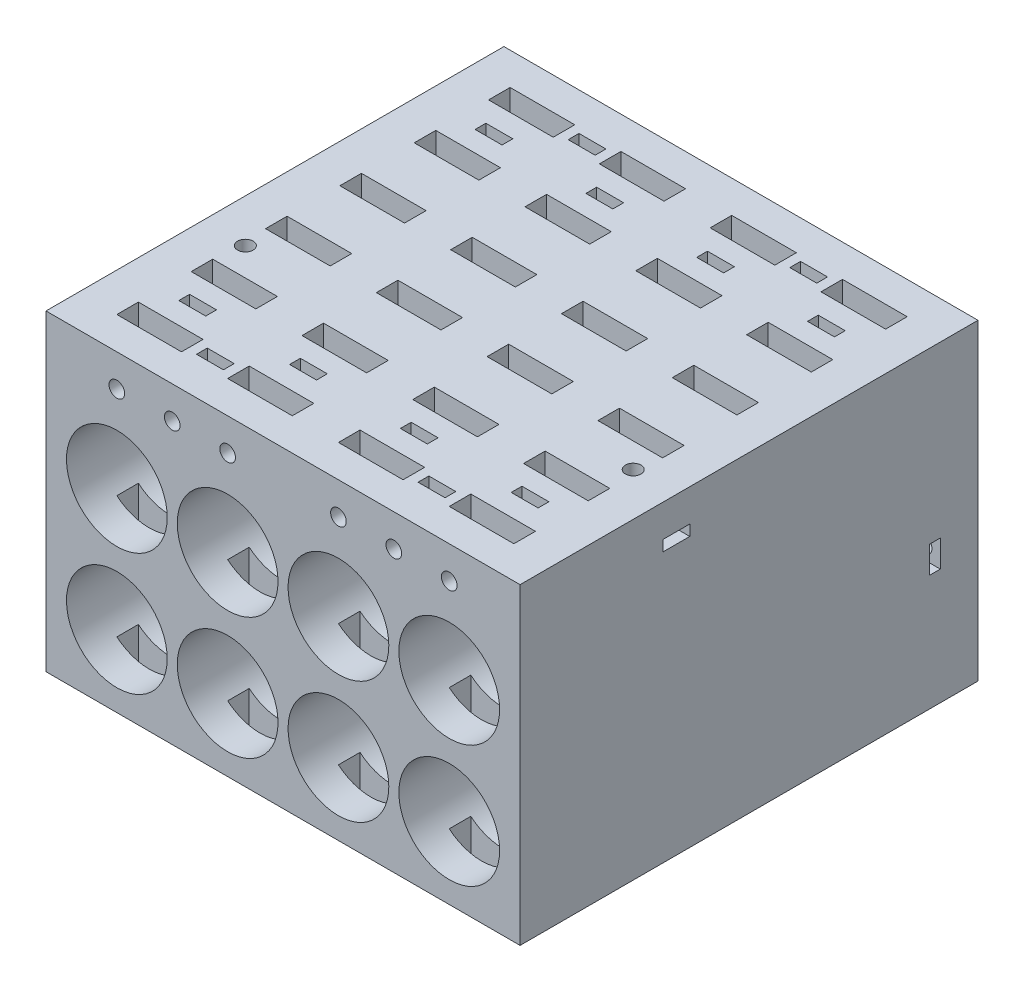
SolidWorks part; units mm, degrees
material "ABS"
ref_plane "Front Plane" through (0, 0, 0) normal (0, 0, 1) x (1, 0, 0)
ref_plane "Top Plane" through (0, 0, 0) normal (0, 1, 0) x (1, 0, 0)
ref_plane "Right Plane" through (0, 0, 0) normal (1, 0, 0) x (0, 0, -1)
sketch "Sketch1" plane through (0, 0, 0) normal (0, 0, 1) x (1, 0, 0)
  line L1 (0, 0) -> (88, 0)
  line L2 (0, 0) -> (0, 58)
  line L3 (0, 58) -> (88, 58)
  line L4 (88, 0) -> (88, 58)
  dimension "D1" = 88
  dimension "D2" = 58
extrude "Boss-Extrude1" add sketch "Sketch1" along normal blind 10
sketch "Sketch2" plane through (0, 0, 10) normal (0, 0, 1) x (1, 0, 0)
  line L0 (3.8, 58) -> (3.8, 0) construction
  line L1 (88, 58) -> (0, 58) construction
  line L2 (0, 0) -> (88, 0) construction
  line L3 (84.2, 58) -> (84.2, 0) construction
  line L4 (0, 4) -> (3.8, 4) construction
  line L5 (0, 58) -> (0, 0) construction
  line L6 (3.8, 4) -> (84.2, 4) construction
  line L7 (84.2, 4) -> (88, 4) construction
  line L8 (88, 0) -> (88, 58) construction
  line L9 (13.15, 13.35) -> (33.7167, 13.35) construction
  line L10 (33.7167, 13.35) -> (54.2833, 13.35) construction
  line L11 (54.2833, 13.35) -> (74.85, 13.35) construction
  line L12 (3.8, 22.7) -> (84.2, 22.7) construction
  line L13 (3.8, 26.7) -> (84.2, 26.7) construction
  line L14 (3.8, 45.4) -> (84.2, 45.4) construction
  line L15 (13.15, 36.05) -> (33.7167, 36.05) construction
  line L16 (33.7167, 36.05) -> (54.2833, 36.05) construction
  line L17 (54.2833, 36.05) -> (74.85, 36.05) construction
  line L19 (0, 0) -> (88, 0)
  line L20 (0, 0) -> (0, 58)
  line L21 (0, 58) -> (88, 58)
  line L22 (88, 0) -> (88, 58)
  circle A0 centre (13.15, 13.35) radius 9.35
  circle A1 centre (33.7167, 13.35) radius 9.35
  circle A2 centre (54.2833, 13.35) radius 9.35
  circle A3 centre (74.85, 13.35) radius 9.35
  circle A4 centre (13.15, 36.05) radius 9.35
  circle A5 centre (33.7167, 36.05) radius 9.35
  circle A6 centre (54.2833, 36.05) radius 9.35
  circle A7 centre (74.85, 36.05) radius 9.35
  dimension "D1" = 18.7
  dimension "D2" = 3.8
  dimension "D3" = 4
  dimension "D4" = 4
extrude "Boss-Extrude2" add sketch "Sketch2" along normal blind 75
sketch "Sketch3" plane through (0, 0, 0) normal (0, -1, 0) x (1, 0, 0)
  line L0 (84.2, 10) -> (65.5, 10) construction
  line L1 (63.6333, 10) -> (44.9333, 10) construction
  line L2 (43.0667, 10) -> (24.3667, 10) construction
  line L3 (22.5, 10) -> (3.8, 10) construction
  line L4 (84.2, 10) -> (65.5, 10) construction
  line L5 (63.6333, 10) -> (44.9333, 10) construction
  line L6 (43.0667, 10) -> (24.3667, 10) construction
  line L7 (22.5, 10) -> (3.8, 10) construction
  line L8 (80.85, 10) -> (80.85, 6)
  line L9 (80.85, 6) -> (68.85, 6)
  line L10 (68.85, 6) -> (68.85, 10)
  line L11 (60.2833, 10) -> (60.2833, 6)
  line L12 (60.2833, 6) -> (48.2833, 6)
  line L13 (48.2833, 6) -> (48.2833, 10)
  line L14 (39.7167, 10) -> (39.7167, 6)
  line L15 (39.7167, 6) -> (27.7167, 6)
  line L16 (27.7167, 6) -> (27.7167, 10)
  line L17 (19.15, 10) -> (19.15, 6)
  line L18 (19.15, 6) -> (7.15, 6)
  line L19 (7.15, 6) -> (7.15, 10)
  line L20 (80.85, 10) -> (68.85, 10)
  line L21 (60.2833, 10) -> (48.2833, 10)
  line L22 (39.7167, 10) -> (27.7167, 10)
  line L23 (19.15, 10) -> (7.15, 10)
  line L24 (0, 85) -> (88, 85) construction
  line L25 (7.15, 79) -> (19.15, 79)
  line L26 (7.15, 79) -> (7.15, 75)
  line L27 (7.15, 75) -> (19.15, 75)
  line L28 (19.15, 79) -> (19.15, 75)
  line L29 (27.7167, 79) -> (39.7167, 79)
  line L30 (27.7167, 79) -> (27.7167, 75)
  line L31 (27.7167, 75) -> (39.7167, 75)
  line L32 (39.7167, 79) -> (39.7167, 75)
  line L33 (48.2833, 79) -> (60.2833, 79)
  line L34 (48.2833, 79) -> (48.2833, 75)
  line L35 (48.2833, 75) -> (60.2833, 75)
  line L36 (60.2833, 79) -> (60.2833, 75)
  line L37 (68.85, 79) -> (80.85, 79)
  line L38 (68.85, 79) -> (68.85, 75)
  line L39 (68.85, 75) -> (80.85, 75)
  line L40 (80.85, 79) -> (80.85, 75)
  point P24 (74.85, 6)
  point P25 (74.85, 10)
  point P26 (54.2833, 6)
  point P27 (54.2833, 10)
  point P28 (33.7167, 6)
  point P29 (33.7167, 10)
  point P30 (13.15, 6)
  point P31 (13.15, 10)
  dimension "D1" = 4
  dimension "D2" = 12
  dimension "D3" = 10
extrude "Cut-Extrude1" cut sketch "Sketch3" against normal through all
hole_wizard "M2.5 Clearance Hole1" positions "Sketch4" profile "Sketch5" hole size "M2.5" standard "ANSI Metric"
sketch "Sketch4" plane through (0, 0, 85) normal (0, 0, 1) x (1, 0, 0)
  line L0 (0, 52) -> (88, 52) construction
  line L1 (0, 58) -> (0, 0) construction
  line L2 (88, 0) -> (88, 58) construction
  line L13 (13.15, 13.35) -> (13.15, 58) construction
  line L14 (88, 58) -> (0, 58) construction
  line L16 (33.7167, 13.35) -> (33.7167, 58) construction
  line L18 (54.2833, 13.35) -> (54.2833, 58) construction
  line L20 (74.85, 13.35) -> (74.85, 58) construction
  point P68 (13.15, 52)
  point P70 (33.7167, 52)
  point P72 (54.2833, 52)
  point P74 (74.85, 52)
  dimension "D1" = 6
sketch "Sketch5" plane through (74.85, 52, 85) normal (1, 0, 0) x (0, -1, 0)
  line L0 (0, 0) -> (0, 22.8712)
  line L1 (0, 22.8712) -> (1.45, 22)
  line L2 (1.45, 22) -> (1.45, 0)
  line L5 (1.45, 0) -> (0, 0)
  line L10 (0, 22.8712) -> (-1.45, 22) construction
  line L11 (0, -6.35) -> (0, 107.95) construction
  dimension "Hole Dia." = 2.9
  dimension "Hole Depth" = 22
  dimension "Drill Angle" = 118
hole_wizard "M2.5 Clearance Hole2" positions "Sketch6" profile "Sketch7" hole size "M2.5" standard "ANSI Metric"
sketch "Sketch6" plane through (0, 0, 0) normal (0, 0, -1) x (-1, 0, 0)
  line L0 (-88, 52) -> (0, 52) construction
  line L1 (-88, 0) -> (-88, 58) construction
  line L2 (0, 58) -> (0, 0) construction
  line L4 (-88, 58) -> (0, 58) construction
  line L5 (-19.15, 58) -> (-7.15, 58) construction
  line L6 (-39.7167, 58) -> (-27.7167, 58) construction
  line L7 (-60.2833, 58) -> (-48.2833, 58) construction
  line L8 (-80.85, 58) -> (-68.85, 58) construction
  line L9 (-19.15, 58) -> (-7.15, 58) construction
  line L10 (-39.7167, 58) -> (-27.7167, 58) construction
  line L11 (-60.2833, 58) -> (-48.2833, 58) construction
  line L12 (-80.85, 58) -> (-68.85, 58) construction
  point P0 (-74.85, 52)
  point P2 (-54.2833, 52)
  point P4 (-33.7167, 52)
  point P6 (-13.15, 52)
  point P33 (-74.85, 58)
  point P35 (-54.2833, 58)
  point P37 (-33.7167, 58)
  point P38 (-13.15, 58)
  dimension "D1" = 6
sketch "Sketch7" plane through (74.85, 52, 0) normal (1, 0, 0) x (0, 1, 0)
  line L0 (0, 0) -> (0, 22.8712)
  line L1 (0, 22.8712) -> (1.45, 22)
  line L2 (1.45, 22) -> (1.45, 0)
  line L5 (1.45, 0) -> (0, 0)
  line L10 (0, 22.8712) -> (-1.45, 22) construction
  line L11 (0, -6.35) -> (0, 107.95) construction
  dimension "Hole Dia." = 2.9
  dimension "Hole Depth" = 22
  dimension "Drill Angle" = 118
sketch "Sketch8" plane through (0, 58, 0) normal (0, 1, 0) x (1, 0, 0)
  line L0 (68.85, -75) -> (80.85, -75) construction
  line L1 (77.35, -71) -> (72.35, -71)
  line L2 (77.35, -71) -> (77.35, -69)
  line L3 (77.35, -69) -> (72.35, -69)
  line L4 (72.35, -71) -> (72.35, -69)
  line L5 (88, -42.5) -> (0, -42.5) construction
  line L6 (88, -85) -> (88, 0) construction
  line L7 (0, -85) -> (0, 0) construction
  line L8 (44, -85) -> (44, 0) construction
  line L9 (88, -85) -> (0, -85) construction
  line L10 (88, 0) -> (0, 0) construction
  line L11 (48.2833, -75) -> (60.2833, -75) construction
  line L12 (56.7833, -71) -> (51.7833, -71)
  line L13 (56.7833, -71) -> (56.7833, -69)
  line L14 (56.7833, -69) -> (51.7833, -69)
  line L15 (51.7833, -71) -> (51.7833, -69)
  line L16 (56.7833, -16) -> (51.7833, -16)
  line L17 (51.7833, -14) -> (51.7833, -16)
  line L18 (56.7833, -14) -> (51.7833, -14)
  line L19 (56.7833, -14) -> (56.7833, -16)
  line L20 (77.35, -16) -> (72.35, -16)
  line L21 (72.35, -14) -> (72.35, -16)
  line L22 (77.35, -14) -> (72.35, -14)
  line L23 (77.35, -14) -> (77.35, -16)
  line L24 (31.2167, -14) -> (31.2167, -16)
  line L25 (31.2167, -14) -> (36.2167, -14)
  line L26 (36.2167, -14) -> (36.2167, -16)
  line L27 (31.2167, -16) -> (36.2167, -16)
  line L28 (10.65, -14) -> (10.65, -16)
  line L29 (10.65, -14) -> (15.65, -14)
  line L30 (15.65, -14) -> (15.65, -16)
  line L31 (10.65, -16) -> (15.65, -16)
  line L32 (10.65, -69) -> (15.65, -69)
  line L33 (15.65, -71) -> (15.65, -69)
  line L34 (10.65, -71) -> (15.65, -71)
  line L35 (10.65, -71) -> (10.65, -69)
  line L36 (31.2167, -69) -> (36.2167, -69)
  line L37 (36.2167, -71) -> (36.2167, -69)
  line L38 (31.2167, -71) -> (36.2167, -71)
  line L39 (31.2167, -71) -> (31.2167, -69)
  line L40 (68.85, -8) -> (60.2833, -8) construction
  line L41 (68.85, -10) -> (68.85, -6) construction
  line L42 (60.2833, -6) -> (60.2833, -10) construction
  line L43 (27.7167, -8) -> (19.15, -8) construction
  line L44 (27.7167, -10) -> (27.7167, -6) construction
  line L45 (19.15, -6) -> (19.15, -10) construction
  line L46 (64.5667, -8) -> (64.5667, 0) construction
  line L47 (23.4333, -8) -> (23.4333, 0) construction
  line L48 (48.2833, -8) -> (39.7167, -8) construction
  line L49 (67.0667, -7) -> (62.0667, -7)
  line L50 (67.0667, -7) -> (67.0667, -9)
  line L51 (67.0667, -9) -> (62.0667, -9)
  line L52 (62.0667, -7) -> (62.0667, -9)
  line L53 (67.0667, -7) -> (62.0667, -9) construction
  line L54 (67.0667, -9) -> (62.0667, -7) construction
  line L55 (25.9333, -7) -> (20.9333, -7)
  line L56 (25.9333, -7) -> (25.9333, -9)
  line L57 (25.9333, -9) -> (20.9333, -9)
  line L58 (20.9333, -7) -> (20.9333, -9)
  line L59 (25.9333, -7) -> (20.9333, -9) construction
  line L60 (25.9333, -9) -> (20.9333, -7) construction
  line L61 (48.2833, -10) -> (48.2833, -6) construction
  line L62 (39.7167, -6) -> (39.7167, -10) construction
  line L63 (19.15, -77) -> (27.7167, -77) construction
  line L64 (19.15, -75) -> (19.15, -79) construction
  line L65 (27.7167, -79) -> (27.7167, -75) construction
  line L66 (60.2833, -77) -> (68.85, -77) construction
  line L68 (68.85, -79) -> (68.85, -75) construction
  line L69 (60.2833, -75) -> (60.2833, -79) construction
  line L70 (20.9333, -78) -> (25.9333, -78)
  line L71 (20.9333, -78) -> (20.9333, -76)
  line L72 (20.9333, -76) -> (25.9333, -76)
  line L73 (25.9333, -78) -> (25.9333, -76)
  line L74 (20.9333, -78) -> (25.9333, -76) construction
  line L75 (20.9333, -76) -> (25.9333, -78) construction
  line L77 (62.0667, -78) -> (67.0667, -78)
  line L78 (62.0667, -78) -> (62.0667, -76)
  line L79 (62.0667, -76) -> (67.0667, -76)
  line L80 (67.0667, -78) -> (67.0667, -76)
  line L81 (62.0667, -78) -> (67.0667, -76) construction
  line L82 (62.0667, -76) -> (67.0667, -78) construction
  point P4 (74.85, -71)
  point P7 (74.85, -75)
  point P26 (54.2833, -75)
  point P27 (54.2833, -71)
  point P88 (23.4333, -77)
  point P91 (64.5667, -77)
  point P101 (64.5667, -77)
  dimension "D1" = 2
  dimension "D2" = 5
  dimension "D3" = 4
  dimension "D4" = 2
extrude "Cut-Extrude2" cut sketch "Sketch8" against normal blind 10
hole_wizard "M2.5 Clearance Hole3" positions "Sketch9" profile "Sketch10" hole size "M2.5" standard "ANSI Metric"
sketch "Sketch9" plane through (0, 0, 0) normal (0, 0, -1) x (-1, 0, 0)
  line L0 (-74.85, 52) -> (-54.2833, 52) construction
  line L1 (-54.2833, 52) -> (-33.7167, 52) construction
  line L2 (-33.7167, 52) -> (-13.15, 52) construction
  point P0 (-64.5667, 52)
  point P4 (-23.4333, 52)
  point P20 (-23.4333, 52)
  point P24 (-64.5667, 52)
sketch "Sketch10" plane through (64.5667, 52, 0) normal (1, 0, 0) x (0, 1, 0)
  line L0 (0, 0) -> (0, 16.8712)
  line L1 (0, 16.8712) -> (1.45, 16)
  line L2 (1.45, 16) -> (1.45, 0)
  line L5 (1.45, 0) -> (0, 0)
  line L10 (0, 16.8712) -> (-1.45, 16) construction
  line L11 (0, -6.35) -> (0, 107.95) construction
  dimension "Hole Dia." = 2.9
  dimension "Hole Depth" = 16
  dimension "Drill Angle" = 118
hole_wizard "M2.5 Clearance Hole4" positions "Sketch11" profile "Sketch12" hole size "M2.5" standard "ANSI Metric"
sketch "Sketch11" plane through (0, 0, 0) normal (0, 0, -1) x (-1, 0, 0)
  line L0 (-80.85, 20.5209) -> (-80.85, 6.1791) construction
  line L1 (-80.85, 43.2209) -> (-80.85, 28.8791) construction
  line L2 (-80.85, 20.5209) -> (-80.85, 6.1791) construction
  line L3 (-80.85, 43.2209) -> (-80.85, 28.8791) construction
  line L4 (-80.85, 28.8791) -> (-80.85, 20.5209) construction
  line L6 (-88, 24) -> (0, 24) construction
  line L7 (-88, 0) -> (-88, 58) construction
  line L8 (0, 58) -> (0, 0) construction
  arc A0 (-80.85, 20.5209) -> (-80.85, 6.1791) centre (-74.85, 13.35) ccw construction
  arc A1 (-80.85, 43.2209) -> (-80.85, 28.8791) centre (-74.85, 36.05) ccw construction
  arc A2 (-80.85, 20.5209) -> (-80.85, 6.1791) centre (-74.85, 13.35) ccw construction
  arc A3 (-80.85, 43.2209) -> (-80.85, 28.8791) centre (-74.85, 36.05) ccw construction
  point P0 (-85, 24)
  point P2 (-3, 24)
  dimension "D1" = 3
  dimension "D2" = 3
sketch "Sketch12" plane through (85, 24, 0) normal (1, 0, 0) x (0, 1, 0)
  line L0 (0, 0) -> (0, 16.8712)
  line L1 (0, 16.8712) -> (1.45, 16)
  line L2 (1.45, 16) -> (1.45, 0)
  line L5 (1.45, 0) -> (0, 0)
  line L10 (0, 16.8712) -> (-1.45, 16) construction
  line L11 (0, -6.35) -> (0, 107.95) construction
  dimension "Hole Dia." = 2.9
  dimension "Hole Depth" = 16
  dimension "Drill Angle" = 118
sketch "Sketch13" plane through (88, 0, 0) normal (1, 0, 0) x (0, 0, -1)
  line L0 (0, 22.55) -> (0, 25.45) construction
  line L1 (0, 22.55) -> (0, 25.45)
  line L2 (0, 24) -> (-8, 24) construction
  line L4 (-9, 21.5) -> (-7, 21.5)
  line L5 (-9, 21.5) -> (-9, 26.5)
  line L6 (-9, 26.5) -> (-7, 26.5)
  line L7 (-7, 21.5) -> (-7, 26.5)
  line L8 (-9, 21.5) -> (-7, 26.5) construction
  line L9 (-9, 26.5) -> (-7, 21.5) construction
  dimension "D1" = 5
  dimension "D2" = 2
  dimension "D3" = 8
extrude "Cut-Extrude3" cut sketch "Sketch13" against normal blind 6 contours L4 L7 L6 L5
ref_plane "Plane1" through (44, 0, 0) normal (1, 0, 0) x (0, 0, -1)
mirror "Mirror1" about plane through (44, 0, 0) normal (1, 0, 0) of "Cut-Extrude3"
hole_wizard "M2.5 Clearance Hole5" positions "Sketch14" profile "Sketch15" hole size "M2.5" standard "ANSI Metric"
sketch "Sketch14" plane through (0, 58, 0) normal (0, 1, 0) x (1, 0, 0)
  line L0 (88, -85) -> (0, -85) construction
  line L1 (88, -85) -> (88, 0) construction
  line L2 (0, -85) -> (0, 0) construction
  point P0 (80, -56)
  point P2 (8, -56)
  dimension "D1" = 29
  dimension "D2" = 8
  dimension "D3" = 8
sketch "Sketch15" plane through (80, 58, 56) normal (1, 0, 0) x (0, 0, 1)
  line L0 (0, 0) -> (0, 12.8712)
  line L1 (0, 12.8712) -> (1.45, 12)
  line L2 (1.45, 12) -> (1.45, 0)
  line L5 (1.45, 0) -> (0, 0)
  line L10 (0, 12.8712) -> (-1.45, 12) construction
  line L11 (0, -6.35) -> (0, 107.95) construction
  dimension "Hole Dia." = 2.9
  dimension "Hole Depth" = 12
  dimension "Drill Angle" = 118
sketch "Sketch16" plane through (88, 0, 0) normal (1, 0, 0) x (0, 0, -1)
  line L0 (-54.55, 58) -> (-57.45, 58) construction
  line L1 (-54.55, 58) -> (-57.45, 58) construction
  line L2 (-85, 58) -> (0, 58) construction
  line L3 (-58.5, 50) -> (-53.5, 50)
  line L4 (-58.5, 50) -> (-58.5, 52)
  line L5 (-58.5, 52) -> (-53.5, 52)
  line L6 (-53.5, 50) -> (-53.5, 52)
  line L7 (-58.5, 50) -> (-53.5, 52) construction
  line L8 (-58.5, 52) -> (-53.5, 50) construction
  point P2 (-56, 51)
  point P8 (-56, 58)
  dimension "D1" = 2
  dimension "D2" = 5
  dimension "D3" = 6
extrude "Cut-Extrude4" cut sketch "Sketch16" against normal blind 10
mirror "Mirror2" about plane through (44, 0, 0) normal (1, 0, 0) of "Cut-Extrude4"
ref_plane "Plane2" through (0, 0, 42.5) normal (0, 0, -1) x (-1, 0, 0)
mirror "Mirror3" about plane through (0, 0, 42.5) normal (0, 0, -1) of "M2.5 Clearance Hole3"
pattern_linear "LPattern1" count 5 spacing 13.8 along (0, 0, -1) of "Cut-Extrude1"
